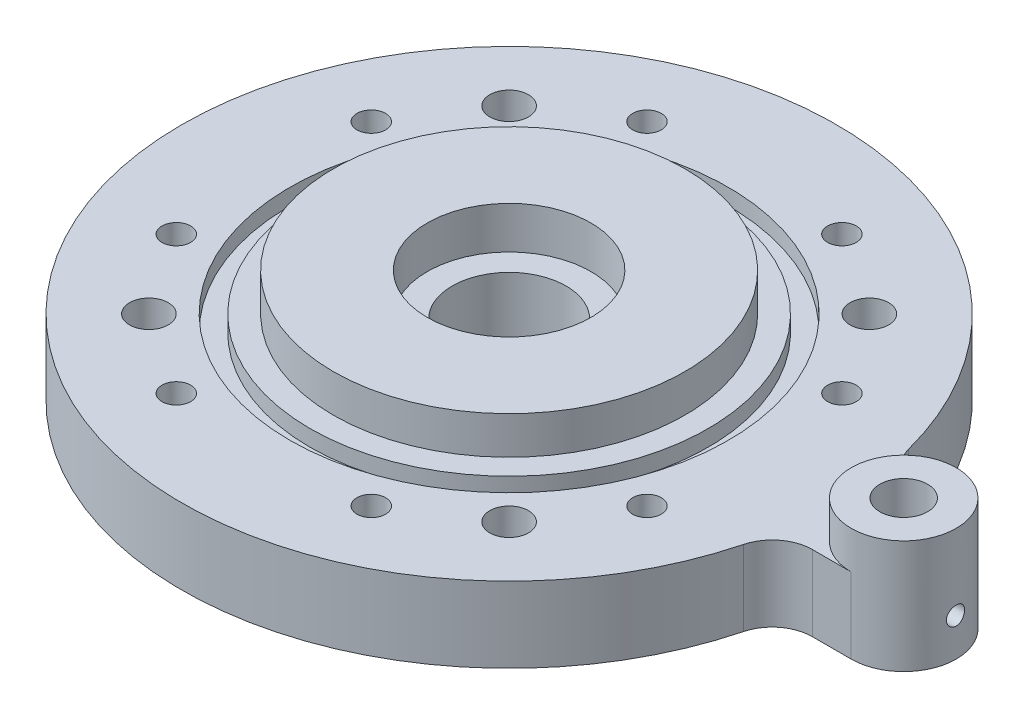
SolidWorks part; units mm, degrees
material "1060 Alloy"
ref_plane "Front" through (0, 0, 0) normal (0, 0, 1) x (1, 0, 0)
ref_plane "Top" through (0, 0, 0) normal (0, 1, 0) x (1, 0, 0)
ref_plane "Right" through (0, 0, 0) normal (1, 0, 0) x (0, 0, -1)
sketch "Sketch1" plane through (0, 0, 0) normal (0, 1, 0) x (1, 0, 0)
  line L0 (59.69, 0) -> (68.8572, 0) construction
  line L1 (62.0793, 9.1672) -> (68.8572, 9.1672)
  line L2 (62.0793, -9.1672) -> (68.8572, -9.1672)
  line L3 (59.69, 0) -> (78.0244, 0) construction
  line L4 (59.69, 0) -> (57.15, 0) construction
  arc A0 (55.3053, 14.403) -> (55.3053, -14.403) centre (0, 0) ccw
  circle A1 centre (0, 0) radius 57.15 construction
  arc A2 (68.8572, -9.1672) -> (68.8572, 9.1672) centre (68.8572, 0) ccw
  arc A3 (55.3053, 14.403) -> (62.0793, 9.1672) centre (62.0793, 16.1672) ccw
  arc A4 (62.0793, -9.1672) -> (55.3053, -14.403) centre (62.0793, -16.1672) ccw
  point P5 (34.5422, 0)
  point P10 (56.41, 9.1672)
  dimension "D1" = 114.3
  dimension "D4" = 7
  dimension "D2" = 18.3344
  dimension "D3" = 18.3344
  dimension "D5" = 2.54
extrude "base" add sketch "Sketch1" along normal blind 13.175
sketch "Sketch2" plane through (0, 13.175, 0) normal (0, 1, 0) x (1, 0, 0)
  line L0 (68.8572, 9.1672) -> (68.8572, -9.1672) construction
  circle A0 centre (0, 0) radius 30.6705
  arc A1 (68.8572, -9.1672) -> (68.8572, 9.1672) centre (68.8572, 0) ccw construction
  circle A2 centre (68.8572, 0) radius 9.1672
  circle A3 centre (68.8572, 0) radius 4.1672
  dimension "D1" = 61.341
  dimension "D2" = 8.3344
sketch "Sketch3" plane through (0, 0, 0) normal (0, -1, 0) x (1, 0, 0)
  line L0 (0, 0) -> (78.0244, 0) construction
  line L1 (0, 0) -> (40.4112, -40.4112) construction
  circle A0 centre (0, 0) radius 44.45 construction
  circle A1 centre (-31.4309, -31.4309) radius 3.3734
  circle A2 centre (-31.4309, 31.4309) radius 3.3734
  circle A3 centre (31.4309, 31.4309) radius 3.3734
  circle A4 centre (31.4309, -31.4309) radius 3.3734
  arc A5 (68.8572, -9.1672) -> (68.8572, 9.1672) centre (68.8572, 0) ccw construction
  arc A6 (55.3053, 14.403) -> (55.3053, -14.403) centre (0, 0) ccw construction
  point P14 (0, 0)
  dimension "D1" = 88.9
  dimension "D2" = 6.7469
  dimension "D4" = 45
  dimension "D3" = 4
extrude "square bolt holes" cut sketch "Sketch3" against normal through all
sketch "Sketch4" plane through (0, 13.175, 0) normal (0, 1, 0) x (1, 0, 0)
  line L0 (0, 0) -> (0, 44.45) construction
  line L1 (0, 44.45) -> (0, 0) construction
  line L2 (0, 0) -> (17.0103, 41.0664) construction
  circle A0 centre (0, 0) radius 44.45 construction
  circle A1 centre (17.0103, 41.0664) radius 2.5
  dimension "D1" = 88.9
  dimension "D3" = 5
  dimension "D2" = 22.5
extrude "housing bolts" cut sketch "Sketch4" against normal blind 44.33
pattern_circular "CirPattern1" count 8 over 360 about axis through (0, 0, 0) along (0, 1, 0) of "housing bolts"
extrude "impeller cavity riser" add sketch "Sketch2" along normal blind 6.59
sketch "Sketch5" plane through (0, 19.765, 0) normal (0, 1, 0) x (1, 0, 0)
  circle A0 centre (0, 0) radius 14.2875
  dimension "D1" = 28.575
extrude "seal bore" cut sketch "Sketch5" against normal blind 7.35
sketch "Sketch6" plane through (0, 12.415, 0) normal (0, 1, 0) x (1, 0, 0)
  circle A0 centre (0, 0) radius 9.9375
  dimension "D1" = 19.875
extrude "bore" cut sketch "Sketch6" against normal blind 39.3
sketch "pressure tap plane alignment" plane through (0, 0, 0) normal (0, -1, 0) x (1, 0, 0)
  line L1 (0, 0) -> (57.15, 0) construction
  line L2 (57.15, 0) -> (57.15, 57.15) construction
  line L3 (57.15, 57.15) -> (0, 57.15) construction
  circle A0 centre (0, 0) radius 57.15 construction
  circle A1 centre (0, 0) radius 57.15 construction
ref_plane "pressure tap plane" through (57.15, 0, 0) normal (1, 0, 0) x (0, 0, -1)
sketch "Sketch9" plane through (57.15, 0, 0) normal (1, 0, 0) x (0, 0, -1)
  line L0 (0, 0) -> (0, 13.175) construction
  line L1 (57.15, 13.175) -> (-57.15, 13.175) construction
  circle A0 centre (0, 6.5875) radius 1.5875
  dimension "D1" = 3.175
extrude "pressure tap" cut sketch "Sketch9" against normal blind 57.15 and the other way through all
sketch "Sketch10" plane through (0, 13.175, 0) normal (0, 1, 0) x (1, 0, 0)
  circle A0 centre (68.8572, 0) radius 1.5875
  dimension "D1" = 3.175
extrude "pressure tap vertical hole" cut sketch "Sketch10" against normal blind 8.175
sketch "Sketch12" plane through (0, 13.175, 0) normal (0, 1, 0) x (1, 0, 0)
  circle A0 centre (0, 0) radius 34.7218
  circle A1 centre (0, 0) radius 38.2524
  dimension "D1" = 76.5048
  dimension "D2" = 69.4436
extrude "o ring feature" cut sketch "Sketch12" against normal blind 2.8245
equation "\"de\" = 0.43in\t\t\t'entrance eye diameter"
equation "\"d2\" = 2.1in \t\t\t'outer diameter of the impeller"
equation "\"d_exit\" = 0.18in \t\t'throat aka d1"
equation "\"theta\" = 12\t\t\t'angle of blades from inner to outer "
equation "\"impeller upper clearance\"= .5mm"
equation "\"impeller horizontal clearance\"= (\"d2\"*1.15 - \"d2\")/2 \t\t'clearance based on D2-D3 ratio for circular volute, ranges 1.15 to 1.2"
equation "\"impeller bottom clearance\"= .5mm"
equation "\"impeller base thickness\"= 2mm"
equation "\"impeller dowel diameter\" = 2mm"
equation "\"impeller bolt head diameter\" = \"m4 head bore diameter\""
equation "\"impeller bolt head depth\" = 4mm"
equation "\"impeller bolt stop depth\" = 3mm"
equation "\"impeller bolt bore\" = \"m4 clearance\""
equation "\"impeller shaft bore depth\" = 12mm"
equation "\"impeller shaft bore\" = 8mm"
equation "\"impeller boss depth\" = \"impeller shaft bore depth\"+\"impeller bolt stop depth\"+\"impeller bolt head depth\"-\"impeller base thickness\""
equation "\"impeller boss diameter\" = \"upper seal ID\""
equation "\"impeller dowel length\" = 2mm*2 + \"impeller shaft bore\""
equation "\"coupler motor shaft hole ID\"= 8mm"
equation "\"coupler OD\"= 17mm"
equation "\"coupler length\"= 25mm"
equation "\"motor OD\" = 64mm"
equation "\"motor shaft diameter\"= 8mm"
equation "\"motor shaft pride\"= 32mm"
equation "\"motor to bearing plate distance\" = \"motor shaft pride\" + 2mm +\"coupler length\"/2"
equation "\"square plate bolt bore\" = \"m8 clearance\""
equation "\"square plate bolt head diameter\" = 13.5mm"
equation "\"square plate bolt pattern diameter\"= 3.5in"
equation "\"motor mount center bore\"= \"coupler OD\"+ 4mm"
equation "\"motor mount post radius\"= ( 3 * \"square plate bolt bore\" ) / 2"
equation "\"motor mount m4 screw hole diameter\"= 4mm"
equation "\"motor mount m4 head diameter\"= 7.25mm"
equation "\"motor mount m4 head depth\"= 4mm"
equation "\"motor mount m4 pattern diamater\" = 30mm"
equation "\"motor mount plate thickness\"= 8mm + \"motor mount m4 head depth\""
equation "\"shaft coupler section diameter\" = 8mm"
equation "\"shaft coupler section length\" = \"motor to bearing plate distance\" - \"motor shaft pride\" - 2mm"
equation "\"shaft bearing section diameter\" = \"bearing ID\""
equation "\"shaft bearing section length\" = \"bearing plate stop depth\" + \"bearing depth\""
equation "\"shaft bearing stop diameter\" = \"bearing ID\" + 4mm"
equation "\"shaft bearing stop length\" = 3mm"
equation "\"impeller cavity center height\"= \"impeller bottom clearance\" + \"impeller upper clearance\" + \"impeller center height\""
equation "\"impeller cavity diameter\"= 2 * \"impeller horizontal clearance\" + \"d2\" \t\t\t\t\t\t\t\t\t'called D3 analytically"
equation "\"impeller cavity outer height\"= \"impeller bottom clearance\" + \"impeller upper clearance\" + \"impeller base thickness\" + \"b2\" \t\t'this is height at impeller diameter d2, not at d3"
equation "\"impeller housing thickness\"= \"impeller housing exit threaded diameter\" + 2*\"impeller housing outlet grip\""
equation "\"impeller housing diameter\" = 4.5in"
equation "\"impeller housing bolt count\" = 8"
equation "\"impeller housing bolt diameter\" = \"m6 clearance\""
equation "\"impeller housing bolt pattern diameter\" = 3.5in"
equation "\"impeller housing threaded inlet diameter\" = 0.71875in \t'this is the 23/32 drill size for 1/2 NPT fitting https://www.mcmaster.com/#50715k269/=176pljy"
equation "\"impeller housing threaded inlet depth\"= .6in"
equation "\"impeller housing exit threaded diameter\"= 0.515625in \t\t'this is the 33/64 drill size for 9/16-18 fitting, expecting swagelok SS-8FK0-1-6STH fitting"
equation "\"impeller housing exit threaded depth\"= 10mm"
equation "\"impeller housing diffuser conical angle\"=10"
equation "\"impeller housing diffuser tangent angle\"=5"
equation "\"impeller housing outlet grip\" = 5mm"
equation "\"D1@Sketch1\"=\"impeller housing diameter\""
equation "\"D1@base\" = \"upper seal plate thickness\""
equation "\"D1@Sketch2\"=\"impeller cavity diameter\""
equation "\"D1@Sketch3\"=\"square plate bolt pattern diameter\""
equation "\"D2@Sketch3\"=\"m8 tap\""
equation "\"D1\"= \"upper seal plate thickness\" - 2mm"
equation "\"D1@Sketch4\"=\"impeller housing bolt pattern diameter\""
equation "\"D2@Sketch4\"=360/\"impeller housing bolt count\"/2"
equation "\"D3@Sketch4\"=\"m6 tap\""
equation "\"D1@CirPattern1\"=\"impeller housing bolt count\""
equation "\"D1@impeller cavity riser\" = \"upper seal plate riser\""
equation "\"D1@Sketch5\" = \"upper seal OD\""
equation "\"D1@seal bore\" = \"upper seal bore\""
equation "\"D1@Sketch6\" = \"upper seal ID\" + 4mm"
equation "\"D1@Sketch9\" = \"upper seal plate pressure hole diameter\""
equation "\"D1@pressure tap\"=\"impeller housing diameter\"/2"
equation "\"de_length\" = 4mm\t\t'entrance eye consistent length"
equation "\"square plate bolt head depth\" = 8mm"
equation "\"shaft impeller section diameter\" = \"impeller shaft bore\""
equation "\"shaft impeller section length\" = \"upper seal plate thickness\" + \"upper seal plate riser\" + \"impeller bottom clearance\" + \"impeller base thickness\" - \"impeller bolt head depth\" - \"impeller bolt stop depth\""
equation "\"impeller housing diffuser final diameter\" = .38in\t\t'aka d2'"
equation "\"D2@Sketch1\" = \"upper seal plate pressure tap diameter\" + \"upper seal plate pressure tap grip\" * 2"
equation "\"D3@Sketch1\" = \"upper seal plate pressure tap diameter\" + \"upper seal plate pressure tap grip\" * 2"
equation "\"D2@pressure tap\"=\"big seal plate pressure tap diameter\"/2+\"big seal plate pressure tap grip\""
equation "\"D2@Sketch2\" = \"upper seal plate pressure tap diameter\""
equation "\"D1@Sketch10\" = \"upper seal plate pressure hole diameter\""
equation "\"D1@pressure tap vertical hole\"= \"upper seal plate thickness\" / 2 + \"upper seal plate pressure hole diameter\" / 2"
equation "\"end mill size\" = 0.375in\t'for 3/8 endmill"
equation "\"m6 clearance\" = 0.234375in\t'this is 15/64 bit = 5.95mm, could use 6mm bit, B bit for 6.04mm or 1/4 bit for 6.35mm"
equation "\"m6 tap\" = 5mm\t\t\t'5mm is appropriate, could use 13/64 or #5,6,7"
equation "\"m6 head bore diameter\" = 11mm\t\t"
equation "\"m6 head bore depth\" = 7mm\t'actual is 6mm"
equation "\"m8 clearance\" = 0.3125in\t'this is 5/16in for 7.93mm, could use 8mm, O,P, or 21/64"
equation "\"m8 tap\" = 0.265625in\t\t'this is 17/64 for 6.746875mm"
equation "\"m8 head bore diameter\" = 14mm"
equation "\"m8 head bore depth\" = 9mm\t'actual is 8mm"
equation "\"ce\" = 3.14*\"de\"\t\t'entrance eye circumference"
equation "\"s_open\" = \"av\"/\"b1\"\t\t'width of open area"
equation "\"impeller center height\" = \"impeller base thickness\" + \"b1\"\t'impeller height at de"
equation "\"impeller outer height\" = \"impeller base thickness\" + \"b2\"\t'impeller height at de"
equation "\"lower seal OD\" = .917in\t\t'this is https://www.mcmaster.com/#9281k121/=174001b"
equation "\"lower seal ID\"= .375in"
equation "\"lower seal depth\" = .625in + .218in"
equation "\"lower seal bore\" = \"lower seal depth\" + 1mm"
equation "\"upper seal OD\" = 1.125in\t'this is https://www.mcmaster.com/#5154t33/=173zuau, needs to be visually inspected before machining!"
equation "\"upper seal ID\"= 0.625in"
equation "\"upper seal depth\"= .25in\t'aka height; these values need to be confirmed by inspection!! We may want to compress the height."
equation "\"upper seal bore\" = \"upper seal depth\" + 1mm"
equation "\"lower seal plate lip depth\" = 2mm"
equation "\"lower seal plate lip ID\" = \"lower seal OD\" - 3mm"
equation "\"lower seal plate thickness\" = \"lower seal plate lip depth\" + \"lower seal bore\""
equation "\"shaft lower seal section diameter\" = \"lower seal ID\""
equation "\"shaft lower seal section length\" = \"lower seal plate thickness\" + 1mm"
equation "\"upper seal plate thickness\" = \"upper seal plate pressure hole diameter\"+10mm"
equation "\"upper seal plate lip ID\" = \"upper seal OD\" - 3mm"
equation "\"upper seal plate riser\" = 6.59mm \t\t'this number needs to be read from the housing file"
equation "\"upper seal plate pressure hole diameter\" = .125in\t'this is 1/8 drill "
equation "\"upper seal plate pressure tap diameter\" = .328125in \t'this is 21/64 drill for a 1/8 ANPT tap"
equation "\"upper seal plate pressure tap grip\" = 5mm\t\t'this is the area around the tap so it doesn't crack"
equation "\"upper seal plate pressure tap depth\" = 12mm"
equation "\"bearing OD\" = 30mm"
equation "\"bearing ID\"= 10mm"
equation "\"bearing depth\"= 9mm"
equation "\"bearing outer race thickness\"= 1mm"
equation "\"bearing inner race thickness\"= 1mm"
equation "\"bearing bore\" = \"bearing depth\" + 1mm"
equation "\"z\" = 8\t\t\t\t'number of blades"
equation "\"b2\" = .2in\t\t\t'tip height from disc surface at d2; slightly higher than d_exit"
equation "\"b1\" = \"b2\" + (\"d2\"/2 - \"de\"/2)*tan(\"theta\") \t\t\t'tip height from disc surface at inlet eye"
equation "\"ae\" = 3.14*(\"de\"^2)/4\t\t'entrance eye area'"
equation "\"av_ratio\" = .325\t\t'ratio of av/ae at N_s of 470, range is .275 to .375, .325 ideal. High ratio means bigger area means smaller blades"
equation "\"av\" = \"ae\"*\"av_ratio\"\t\t'area between just two blades"
equation "\"s\"=\"ce\" - \"z\"*\"s_open\""
equation "\"bearing plate stop ID\" = \"bearing OD\" - 4mm"
equation "\"bearing plate stop depth\" = 3mm"
equation "\"bearing plate thickness\" = \"bearing bore\" + \"bearing plate stop depth\" + \"shaft bearing stop length\""
equation "\"m4 clearance\" = 0.171875in \t'this is 11/64 bit for 4.36mm"
equation "\"m4 tap\" = 0.125in\t\t'this is 1/8 bit for 3.17mm"
equation "\"m4 head bore diameter\" = 7.5mm"
equation "\"m4 head bore depth\" = 5mm\t'actual is ~4mm"
equation "\"big o-ring thickness\" = .139in"
equation "\"big o-ring OD\" = 2.734in"
equation "\"big o-ring ID\" = 3.012in"
equation "\"big o-ring groove depth\" = \"big o-ring thickness\"*4/5"
equation "\"D1@Sketch12\"=\"big o-ring ID\""
equation "\"D2@Sketch12\"=\"big o-ring OD\""
equation "\"D1@o ring feature\" = \"big o-ring groove depth\""
equation "\"min blade thickness\" = .15in"
equation "\"diffuser cartridge OD\" =.75in"
equation "\"diffuser flange bolt pattern diameter\" = 1.4in"
